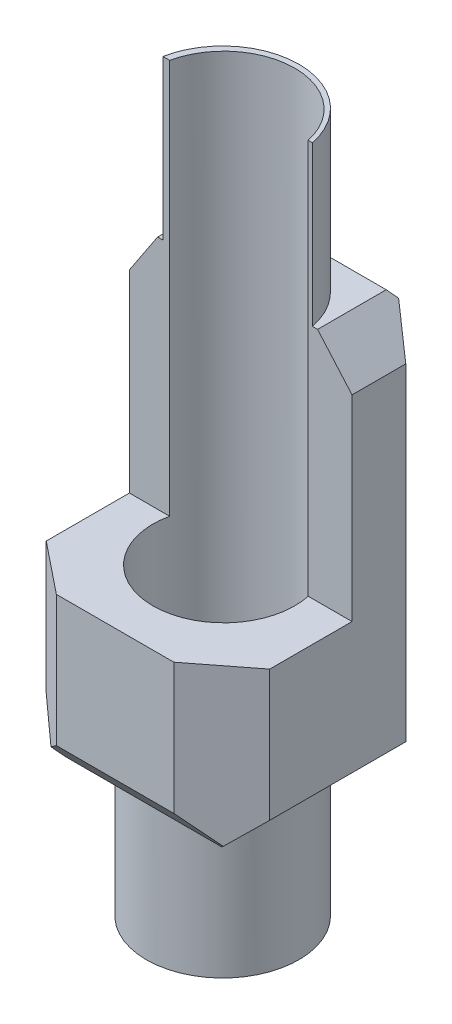
SolidWorks part; units mm, degrees
ref_plane "Front Plane" through (0, 0, 0) normal (0, 0, 1) x (1, 0, 0)
ref_plane "Top Plane" through (0, 0, 0) normal (0, 1, 0) x (1, 0, 0)
ref_plane "Right Plane" through (0, 0, 0) normal (1, 0, 0) x (0, 0, -1)
sketch "Sketch1" plane through (0, 0, 0) normal (0, 1, 0) x (1, 0, 0)
  line L1 (0, 0) -> (-100, 0)
  line L2 (0, 0) -> (0, 100)
  line L3 (0, 100) -> (-100, 100)
  line L4 (-100, 0) -> (-100, 100)
  dimension "D1" = 100
  dimension "D2" = 100
extrude "Boss-Extrude1" add sketch "Sketch1" along normal blind 180
sketch "Sketch2" plane through (0, 180, 0) normal (0, 1, 0) x (1, 0, 0)
  circle A0 centre (-51.3773, 49.0765) radius 34.2578
  point P2 (-49.1037, 52.2166)
  point P3 (-48.8771, 51.8469)
  point P4 (-51.3773, 49.0765)
extrude "Boss-Extrude2" add sketch "Sketch2" along normal mid plane 700
sketch "Sketch3" plane through (0, 0, 0) normal (1, 0, 0) x (0, 0, -1)
  line L1 (-18.5833, 361.0481) -> (133.4231, 361.0481)
  line L2 (-18.5833, 361.0481) -> (-18.5833, 643.5005)
  line L3 (-18.5833, 643.5005) -> (133.4231, 643.5005)
  line L4 (133.4231, 361.0481) -> (133.4231, 643.5005)
extrude "Cut-Extrude2" cut sketch "Sketch3" against normal blind 400
sketch "Sketch4" plane through (0, 0, 0) normal (1, 0, 0) x (0, 0, -1)
  line L0 (12.982, 0) -> (-8.9942, 25.8281)
  line L1 (-8.9942, 25.8281) -> (-18.5645, -15.2595)
  line L2 (-18.5645, -15.2595) -> (12.982, 0)
  line L3 (85.0725, -1.4481) -> (109.2376, 19.1131)
  line L4 (109.2376, 19.1131) -> (115.92, -3.2674)
  line L5 (115.92, -3.2674) -> (85.0725, -1.4481)
  line L6 (12.982, 180) -> (-8.9942, 148.5376)
  line L7 (-8.9942, 148.5376) -> (-15.4182, 193.2193)
  line L8 (-15.4182, 193.2193) -> (12.982, 180)
  line L9 (85.0725, 181.8543) -> (103.8412, 159.7959)
  line L10 (103.8412, 159.7959) -> (106.1325, 198.6474)
  line L11 (106.1325, 198.6474) -> (85.0725, 181.8543)
extrude "Cut-Extrude3" cut sketch "Sketch4" against normal blind 400
sketch "Sketch5" plane through (0, 0, 0) normal (0, 0, 1) x (1, 0, 0)
  line L0 (-85.6233, 0) -> (-106.3704, 21.4264)
  line L1 (-106.3704, 21.4264) -> (-122.2889, 3.2093)
  line L2 (-122.2889, 3.2093) -> (-93.5263, -19.8847)
  line L3 (-93.5263, -19.8847) -> (-85.6233, 0)
  line L4 (-15.695, 0) -> (0, 15.2574)
  line L5 (0, 15.2574) -> (12.1227, 15.2574)
  line L6 (12.1227, 15.2574) -> (10.5631, -19.8847)
  line L7 (10.5631, -19.8847) -> (-15.695, 0)
  line L8 (-87.1665, 180.2481) -> (-106.3704, 151.2911)
  line L9 (-106.3704, 151.2911) -> (-117.7055, 200.5011)
  line L10 (-117.7055, 200.5011) -> (-87.1665, 180.2481)
  line L11 (-15.695, 180.2481) -> (7.8338, 153.2796)
  line L12 (7.8338, 153.2796) -> (0, 193.9412)
  line L13 (0, 193.9412) -> (-15.695, 180.2481)
extrude "Cut-Extrude4" cut sketch "Sketch5" against normal blind 400
sketch "Sketch6" plane through (0, 180, 0) normal (0, 1, 0) x (1, 0, 0)
  line L1 (-112.387, 28.4004) -> (-64.2613, -10.2128)
  line L2 (-112.387, 28.4004) -> (-124.6497, -15.5119)
  line L3 (-124.6497, -15.5119) -> (-84.4064, -15.5119)
  line L4 (-64.2613, -10.2128) -> (-84.4064, -15.5119)
  line L5 (-97.0655, 135.8618) -> (-119.3755, 77.7927)
  line L6 (-97.0655, 135.8618) -> (-66.4287, 110.5752)
  line L7 (-66.4287, 110.5752) -> (-118.0433, 64.3476)
  line L8 (-119.3755, 77.7927) -> (-118.0433, 64.3476)
  line L9 (-24.6964, -21.8158) -> (11.0921, -8.9736)
  line L10 (-24.6964, -21.8158) -> (-38.5316, -11.1392)
  line L11 (-38.5316, -11.1392) -> (17.4283, 32.3938)
  line L12 (11.0921, -8.9736) -> (17.4283, 32.3938)
  line L13 (-17.4455, 140.8044) -> (35.4175, 107.2625)
  line L14 (-17.4455, 140.8044) -> (-31.7244, 103.6253)
  line L15 (-31.7244, 103.6253) -> (9.3055, 72.9964)
  line L16 (35.4175, 107.2625) -> (9.3055, 72.9964)
  point P4 (-17.4455, 140.8044)
  point P5 (-30.2763, 114.984)
  point P6 (35.4175, 107.2625)
  point P19 (-30.6265, 106.484)
  point P20 (-11.2095, 88.3109)
extrude "Cut-Extrude5" cut sketch "Sketch6" against normal blind 400
sketch "Sketch7" plane through (0, 0, 0) normal (0, 0, 1) x (1, 0, 0)
  line L1 (-146.2029, -210.0437) -> (13.9564, -210.0437)
  line L2 (-146.2029, -210.0437) -> (-146.2029, -62.6814)
  line L3 (-146.2029, -62.6814) -> (13.9564, -62.6814)
  line L4 (13.9564, -210.0437) -> (13.9564, -62.6814)
extrude "Cut-Extrude6" cut sketch "Sketch7" against normal blind 400
sketch "Sketch8" plane through (0, 0, 0) normal (0, 0, 1) x (1, 0, 0)
  line L1 (-127.1965, 251.4288) -> (20.1142, 251.4288)
  line L2 (-127.1965, 251.4288) -> (-127.1965, 413.4677)
  line L3 (-127.1965, 413.4677) -> (20.1142, 413.4677)
  line L4 (20.1142, 251.4288) -> (20.1142, 413.4677)
extrude "Cut-Extrude7" cut sketch "Sketch8" against normal blind 400
sketch "Sketch9" plane through (0, 251.4288, 0) normal (0, 1, 0) x (1, 0, 0)
  circle A0 centre (-50.809, 49.032) radius 31.8473
  point P2 (-50.6049, 49.6989)
  point P3 (-51.6378, 48.9774)
  point P4 (-50.809, 49.032)
extrude "Cut-Extrude8" cut sketch "Sketch9" against normal blind 400
sketch "Sketch10" plane through (-100, 0, 0) normal (-1, 0, 0) x (0, 0, 1)
  line L1 (-55.8114, 74.0839) -> (84.4096, 74.0839)
  line L2 (-55.8114, 74.0839) -> (-55.8114, 286.1174)
  line L3 (-55.8114, 286.1174) -> (84.4096, 286.1174)
  line L4 (84.4096, 74.0839) -> (84.4096, 286.1174)
extrude "Cut-Extrude9" cut sketch "Sketch10" against normal blind 400
